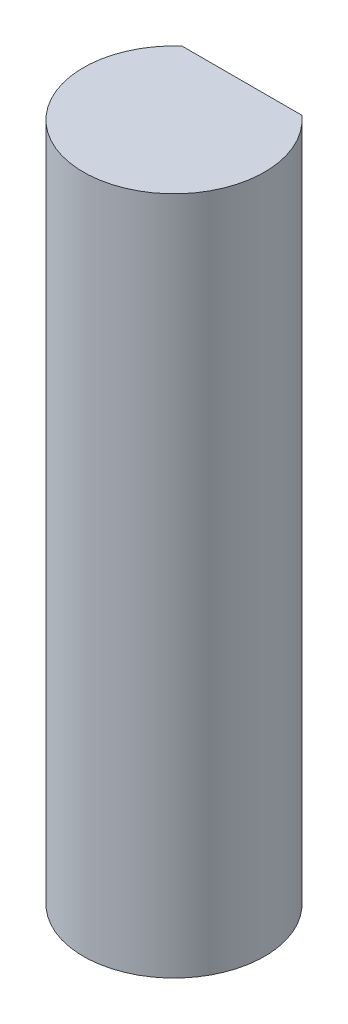
SolidWorks part; units mm, degrees
ref_plane "Front Plane" through (0, 0, 0) normal (0, 0, 1) x (1, 0, 0)
ref_plane "Top Plane" through (0, 0, 0) normal (0, 1, 0) x (1, 0, 0)
ref_plane "Right Plane" through (0, 0, 0) normal (1, 0, 0) x (0, 0, -1)
sketch "Sketch1" plane through (0, 0, 0) normal (0, 1, 0) x (1, 0, 0)
  line L0 (1.3229, 1.5) -> (-1.3229, 1.5)
  line L1 (-2.2, 0) -> (2.2, 0) construction
  arc A0 (-1.3229, 1.5) -> (1.3229, 1.5) centre (0, 0) ccw
  dimension "D1" = 2
  dimension "D2" = 1.5
extrude "Boss-Extrude1" add sketch "Sketch1" along normal mid plane 15
equation "\"height\"= 15"
equation "\"D1@Boss-Extrude1\"=\"height\""
